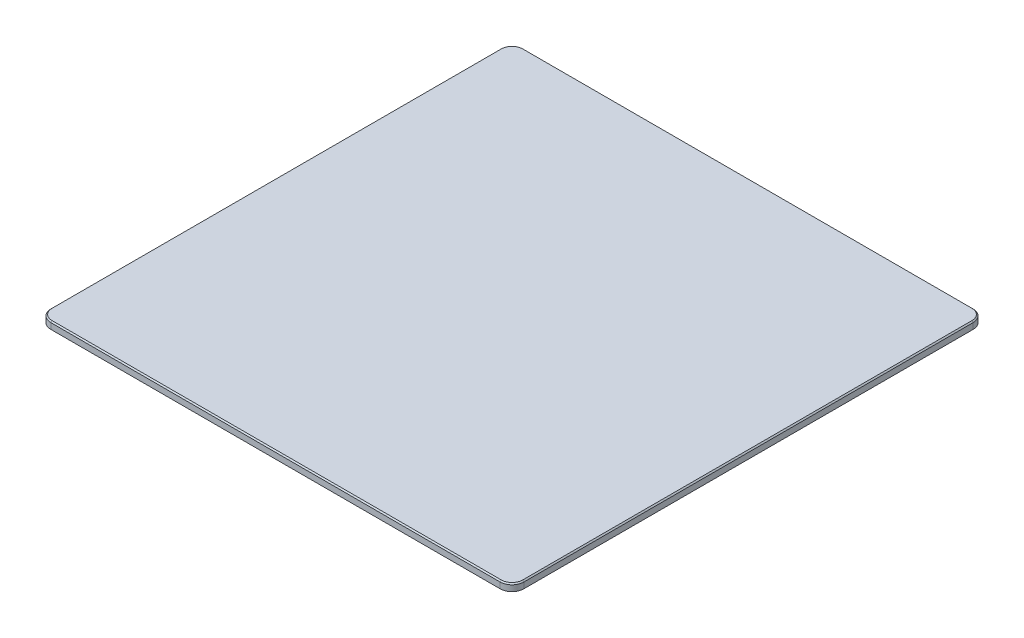
SolidWorks part; units mm, degrees
ref_plane "Alzado" through (0, 0, 0) normal (0, 0, 1) x (1, 0, 0)
ref_plane "Planta" through (0, 0, 0) normal (0, 1, 0) x (1, 0, 0)
ref_plane "Vista lateral" through (0, 0, 0) normal (1, 0, 0) x (0, 0, -1)
sketch "Croquis1" plane through (0, 0, 0) normal (0, 1, 0) x (1, 0, 0)
  line L1 (-100, -100) -> (100, -100)
  line L2 (-100, -100) -> (-100, 100)
  line L3 (-100, 100) -> (100, 100)
  line L4 (100, -100) -> (100, 100)
  line L5 (-100, -100) -> (100, 100) construction
  line L6 (-100, 100) -> (100, -100) construction
  point P0 (0, 0)
  dimension "D1" = 200
  dimension "D2" = 200
extrude "Saliente-Extruir1" add sketch "Croquis1" along normal blind 3
fillet "Redondeo1" radius 5 4 edges at (-100, 1.5, -100) (100, 1.5, -100) (100, 1.5, 100) (-100, 1.5, 100)
chamfer "Chaflán1" distance 0.5 angle 45 8 edges at (98.5355, 3, -98.5355) (100, 3, 0) (98.5355, 3, 98.5355) (0, 3, 100) (-98.5355, 3, 98.5355) (-100, 3, 0) (-98.5355, 3, -98.5355) (0, 3, -100)
